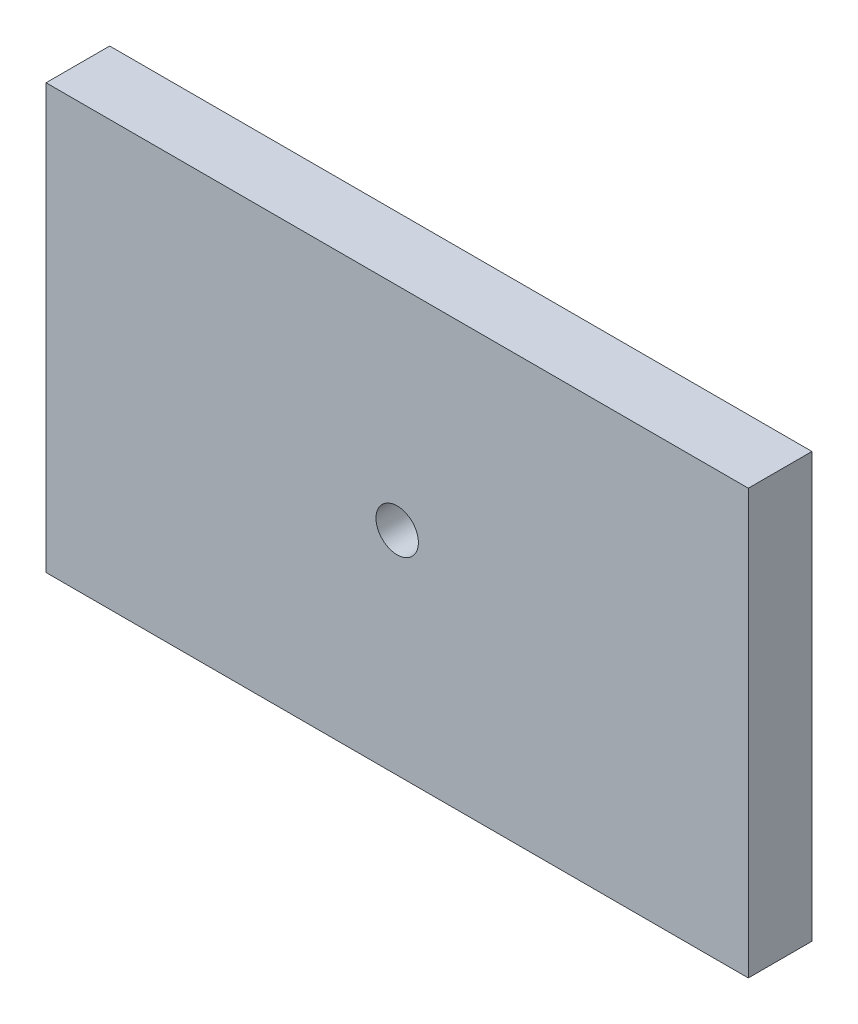
SolidWorks part; units mm, degrees
ref_plane "Alzado" through (0, 0, 0) normal (0, 0, 1) x (1, 0, 0)
ref_plane "Planta" through (0, 0, 0) normal (0, 1, 0) x (1, 0, 0)
ref_plane "Vista lateral" through (0, 0, 0) normal (1, 0, 0) x (0, 0, -1)
sketch "Croquis1" plane through (0, 0, 0) normal (0, 0, 1) x (1, 0, 0)
  line L1 (-16.555, -10) -> (16.555, -10)
  line L2 (-16.555, -10) -> (-16.555, 10)
  line L3 (-16.555, 10) -> (16.555, 10)
  line L4 (16.555, -10) -> (16.555, 10)
  line L5 (-16.555, -10) -> (16.555, 10) construction
  line L6 (-16.555, 10) -> (16.555, -10) construction
  circle A0 centre (0, 0) radius 1
  point P0 (0, 0)
  dimension "D1" = 33.11
  dimension "D2" = 20
extrude "Saliente-Extruir1" add sketch "Croquis1" along normal blind 3
